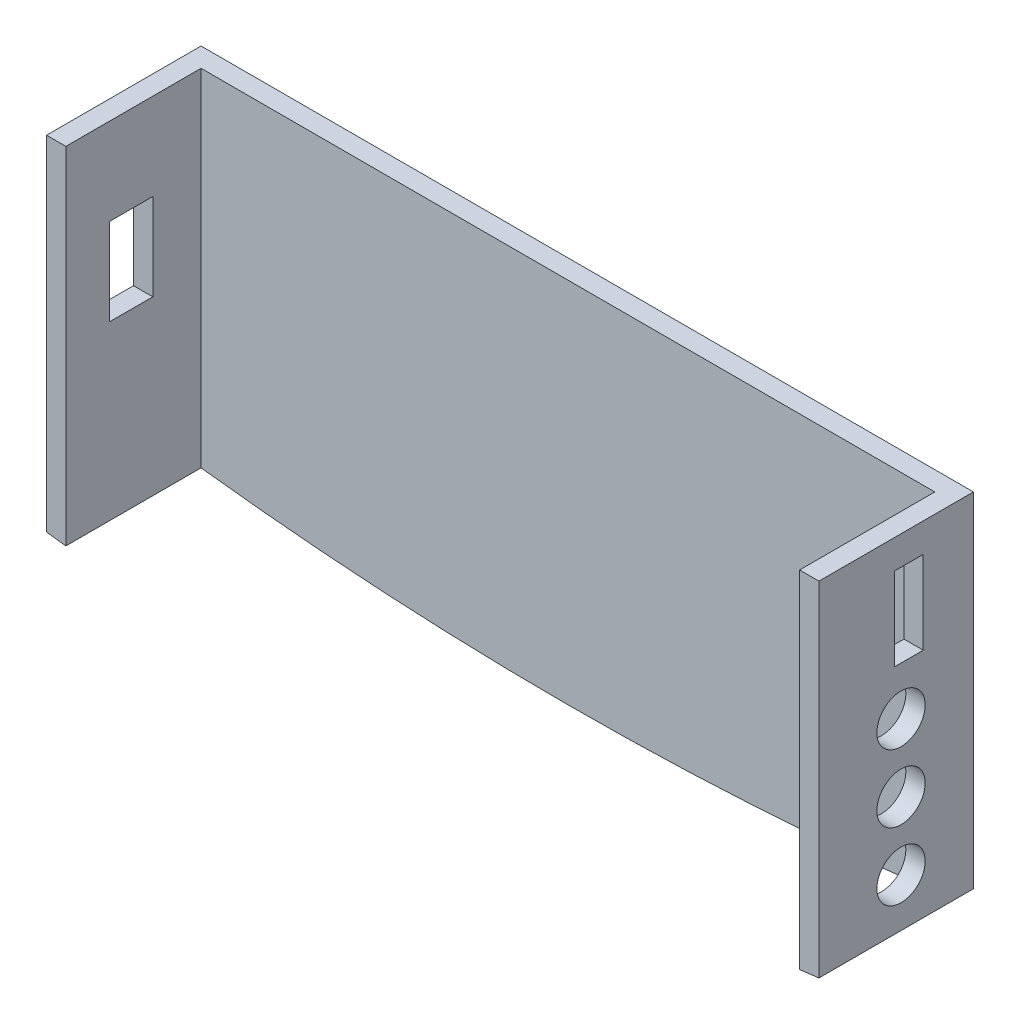
SolidWorks part; units mm, degrees
ref_plane "前视基准面" through (0, 0, 0) normal (0, 0, 1) x (1, 0, 0)
ref_plane "上视基准面" through (0, 0, 0) normal (0, 1, 0) x (1, 0, 0)
ref_plane "右视基准面" through (0, 0, 0) normal (1, 0, 0) x (0, 0, -1)
other "Configuration Table"
sketch "草图1" plane through (0, 0, 0) normal (0, 0, 1) x (1, 0, 0)
  line L1 (-10.4206, -29.2673) -> (-90.4206, -29.2673)
  line L2 (-10.4206, -29.2673) -> (-10.4206, 6.3327)
  line L3 (-10.4206, 6.3327) -> (-90.4206, 6.3327)
  line L4 (-90.4206, -29.2673) -> (-90.4206, 6.3327)
  line L5 (-10.4206, -29.2673) -> (-90.4206, 6.3327) construction
  line L6 (-10.4206, 6.3327) -> (-90.4206, -29.2673) construction
  arc A0 (-90.4206, -29.2673) -> (-10.4206, -29.2673) centre (-50.4206, 289.9866) ccw
  point P0 (-50.4206, -11.4673)
  dimension "D3" = 321.75
  dimension "D1" = 80
  dimension "D2" = 35.6
extrude "凸台-拉伸1" add sketch "草图1" along normal blind 16 contours L4 L1 L2 L3 | L1 A0
shell "抽壳1" thickness 2
sketch "草图2" plane through (-90.4206, 0, 0) normal (-1, 0, 0) x (0, 0, 1)
  line L6 (0, -29.2673) -> (0, 6.3327) construction
  line L7 (7, -2.6673) -> (11.5, -2.6673)
  line L8 (7, -2.6673) -> (7, -11.6673)
  line L9 (7, -11.6673) -> (11.5, -11.6673)
  line L10 (11.5, -2.6673) -> (11.5, -11.6673)
  line L11 (16, 6.3327) -> (0, 6.3327) construction
  dimension "D1" = 4.5
  dimension "D2" = 9
  dimension "D3" = 9
  dimension "D9" = 7
extrude "切除-拉伸3" cut sketch "草图2" against normal up to next
sketch "草图6" plane through (-10.4206, 0, 0) normal (1, 0, 0) x (0, 0, -1)
  line L1 (-8.2, 3.3327) -> (-5.2, 3.3327)
  line L2 (-8.2, 3.3327) -> (-8.2, -5.2673)
  line L3 (-8.2, -5.2673) -> (-5.2, -5.2673)
  line L4 (-5.2, 3.3327) -> (-5.2, -5.2673)
  line L8 (-16, 6.3327) -> (0, 6.3327) construction
  line L11 (0, -29.2673) -> (0, 6.3327) construction
  circle A0 centre (-7.5, -10.2673) radius 2.5
  circle A1 centre (-7.5, -17.2673) radius 2.5
  circle A2 centre (-7.5, -24.2673) radius 2.5
  dimension "D5" = 5
  dimension "D6" = 5
  dimension "D7" = 5
  dimension "D1" = 3
  dimension "D2" = 8.6
  dimension "D3" = 7.5
  dimension "D4" = 3
  dimension "D8" = 5
  dimension "D9" = 7
  dimension "D10" = 7
extrude "切除-拉伸4" cut sketch "草图6" against normal up to next
